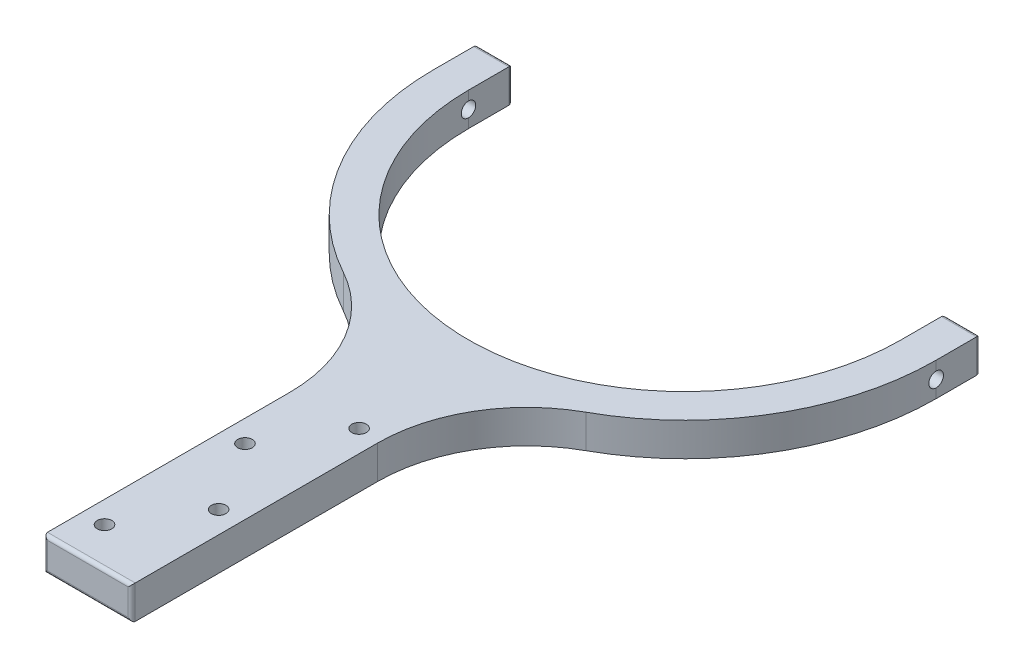
SolidWorks part; units mm, degrees
ref_plane "Plano frontal" through (0, 0, 0) normal (0, 0, 1) x (1, 0, 0)
ref_plane "Plano superior" through (0, 0, 0) normal (0, 1, 0) x (1, 0, 0)
ref_plane "Plano direito" through (0, 0, 0) normal (1, 0, 0) x (0, 0, -1)
sketch "Esboço2" plane through (0, 0, 0) normal (0, 1, 0) x (1, 0, 0)
  line L2 (-25, -200) -> (-25, -340)
  line L3 (-25, -340) -> (25, -340)
  line L4 (25, -340) -> (25, -200)
  line L5 (-143.2, 0) -> (-143.2, 25)
  line L6 (-143.2, 25) -> (-123.2, 25)
  line L7 (-123.2, 25) -> (-123.2, 0)
  line L8 (123.2, 0) -> (123.2, 25)
  line L9 (123.2, 25) -> (143.2, 25)
  line L10 (143.2, 25) -> (143.2, 0)
  arc A0 (-123.2, 0) -> (123.2, 0) centre (0, 0) ccw
  arc A1 (-143.2, 0) -> (-69.0612, -125.4464) centre (0, 0) ccw
  arc A2 (143.2, 0) -> (69.0612, -125.4464) centre (0, 0) cw
  arc A3 (69.0612, -125.4464) -> (25, -200) centre (110.1047, -200) ccw
  arc A4 (-25, -200) -> (-69.0612, -125.4464) centre (-110.1047, -200) ccw
  dimension "D1" = 123.2
  dimension "D4" = 25
  dimension "D2" = 20
  dimension "D3" = 20
  dimension "D5" = 25
  dimension "D6" = 50
  dimension "D7" = 140
  dimension "D8" = 25
  dimension "D9" = 340
extrude "Ressalto-extrusão1" add sketch "Esboço2" along normal blind 19
fillet "Filete2" radius 2 4 edges at (-123.2, 9.5, -25) (-133.2, 0, -25) (-143.2, 9.5, -25) (-133.2, 19, -25)
fillet "Filete3" radius 2 4 edges at (123.2, 9.5, -25) (133.2, 0, -25) (133.2, 19, -25) (143.2, 9.5, -25)
fillet "Filete4" radius 2 4 edges at (25, 9.5, 340) (0, 0, 340) (-25, 9.5, 340) (0, 19, 340)
sketch "Esboço5" plane through (0, 19, 0) normal (0, 1, 0) x (1, 0, 0)
  line L0 (-25, -200) -> (-25, -338) construction
  line L1 (-25, -338) -> (25, -338) construction
  line L2 (25, -338) -> (25, -200) construction
  point P0 (-12.5, -318)
  point P1 (12.5, -278)
  point P2 (12.5, -198)
  point P3 (-12.5, -238)
  point P6 (12.5, -318)
  point P7 (12.3896, -288.7845)
  point P10 (12.5, -291.0203)
  point P13 (12.5, -297.0848)
  point P14 (0, 0)
  point P15 (12.5, -229.9202)
  point P16 (67.398, -225.995)
  point P17 (87.8963, -235.59)
  point P18 (12.5, -279.6395)
  point P19 (0, 0)
  point P20 (-12.5, -239.079)
  dimension "D1" = 12.5
  dimension "D2" = 12.5
  dimension "D3" = 80
  dimension "D4" = 20
  dimension "D5" = 80
  dimension "D6" = 40
hole_wizard "Furo roscado para conduíte de M8x1.252" positions "3DSketch4" profile "Esboço7" tap size "M8x1.25" standard "Helicoil® Metric" end condition through all
sketch3d "3DSketch4"
  point P0 (-12.5, 19, 318)
  point P4 (12.5, 19, 278)
  point P7 (12.5, 19, 198)
  point P10 (-12.5, 19, 238)
sketch "Esboço7" plane through (-12.5, 19, 318) normal (1, 0, 0) x (0, 0, 1)
  line L0 (0, 0) -> (0, 19)
  line L1 (0, 19) -> (4.15, 19)
  line L2 (4.15, 19) -> (4.15, 0)
  line L5 (4.15, 0) -> (0, 0)
  line L11 (0, -6.35) -> (0, 107.95) construction
  dimension "Thru Tap Drill Dia." = 8.3
  dimension "Thru Tap Drill Depth" = 19
cosmetic thread "Rosca de furo3" parameters "D1"=19, "D2"=9.787
cosmetic thread "Rosca de furo4" parameters "D1"=19, "D2"=9.787
cosmetic thread "Rosca de furo5" parameters "D1"=19, "D2"=9.787
cosmetic thread "Rosca de furo6" parameters "D1"=19, "D2"=9.787
sketch "Esboço8" plane through (143.2, 0, 0) normal (1, 0, 0) x (0, 0, -1)
  line L0 (0, 19) -> (0, 0) construction
  point P0 (0, 9.5)
sketch "Esboço10" plane through (-143.2, 0, 0) normal (-1, 0, 0) x (0, 0, 1)
  line L0 (0, 19) -> (0, 0) construction
  point P0 (0, 9.5)
hole_wizard "Furo roscado para conduíte de M8x1.251" positions "3DSketch6" profile "Esboço11" tap size "M8x1.25" standard "Helicoil® Metric"
sketch3d "3DSketch6"
  point P0 (143.2, 9.5, 0)
  point P3 (-143.2, 9.5, 0)
sketch "Esboço11" plane through (143.2, 9.5, 0) normal (0, 1, 0) x (0, 0, -1)
  line L0 (0, 0) -> (0, 27.4936)
  line L1 (0, 27.4936) -> (4.15, 25)
  line L2 (4.15, 25) -> (4.15, 0)
  line L5 (4.15, 0) -> (0, 0)
  line L10 (0, 27.4936) -> (-4.15, 25) construction
  line L11 (0, -6.35) -> (0, 107.95) construction
  dimension "Tap Drill Dia." = 8.3
  dimension "Tap Drill Depth" = 25
  dimension "Drill Angle" = 118
cosmetic thread "Rosca de furo1" parameters "D1"=25, "D2"=9.787
cosmetic thread "Rosca de furo2" parameters "D1"=25, "D2"=9.787
